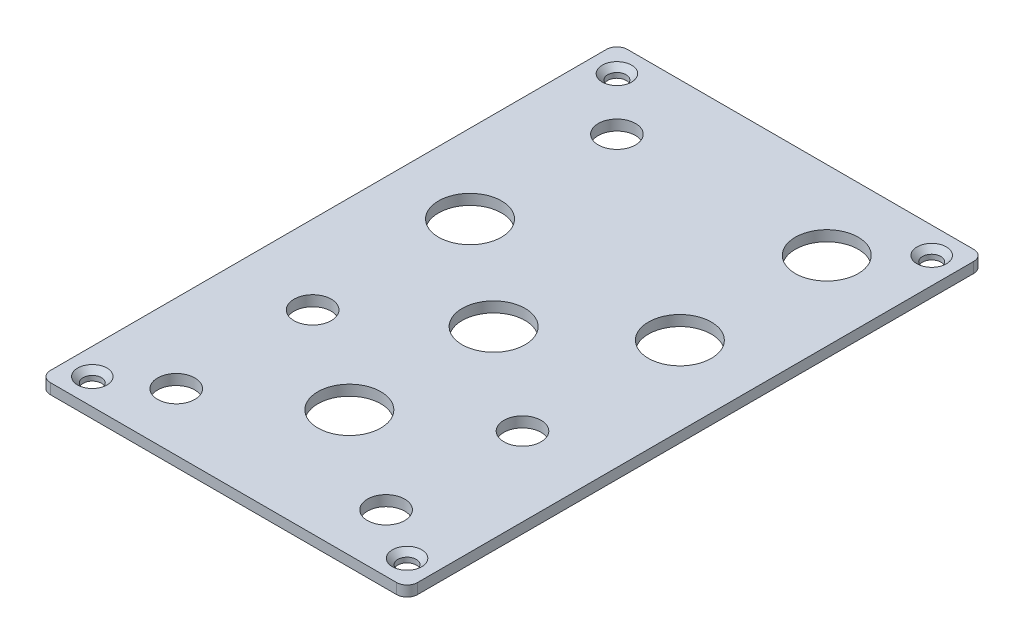
SolidWorks part; units mm, degrees
ref_plane "Front Plane" through (0, 0, 0) normal (0, 0, 1) x (1, 0, 0)
ref_plane "Top Plane" through (0, 0, 0) normal (0, 1, 0) x (1, 0, 0)
ref_plane "Right Plane" through (0, 0, 0) normal (1, 0, 0) x (0, 0, -1)
sketch "Face Plate" plane through (0, 0, 0) normal (0, 1, 0) x (1, 0, 0)
  line L1 (35, -55) -> (-35, -55)
  line L2 (35, -55) -> (35, 55)
  line L3 (35, 55) -> (-35, 55)
  line L4 (-35, -55) -> (-35, 55)
  line L5 (35, -55) -> (-35, 55) construction
  line L6 (35, 55) -> (-35, -55) construction
  point P0 (0, 0)
  dimension "D1" = 70
  dimension "D2" = 110
extrude "Face Plate Ext" add sketch "Face Plate" along normal blind 2
sketch "Buttons" plane through (0, 2, 0) normal (0, 1, 0) x (1, 0, 0)
  line L0 (-20, -18) -> (-20, -44) construction
  line L1 (-35, 55) -> (-35, -55) construction
  line L2 (-20, -31) -> (0, -31) construction
  line L3 (35, 55) -> (-35, 55) construction
  line L4 (35, -55) -> (35, 55) construction
  line L5 (-20, -18) -> (20, -18) construction
  line L6 (0, -18) -> (0, -31) construction
  circle A0 centre (-20, 12) radius 6
  circle A1 centre (20, 12) radius 6
  circle A2 centre (-20, -18) radius 3.55
  circle A3 centre (-20, -44) radius 3.55
  circle A4 centre (-20, 40) radius 3.55
  circle A5 centre (20, -18) radius 3.55
  circle A6 centre (20, -44) radius 3.55
  circle A7 centre (20, 40) radius 6
  circle A8 centre (0, -31) radius 6
  circle A9 centre (0, -3.5) radius 6
  dimension "D6" = 12
  dimension "D7" = 7.1
  dimension "D5" = 7.1
  dimension "D9" = 14.5
  dimension "D2" = 15
  dimension "D3" = 15
  dimension "D4" = 15
  dimension "D8" = 28
  dimension "D10" = 15
  dimension "D11" = 15
  dimension "D12" = 15
  dimension "D13" = 26
  dimension "D14" = 30
extrude "Buttons CUT" cut sketch "Buttons" against normal blind 10
sketch "M3 Top Screw" plane through (0, 2, 0) normal (0, 1, 0) x (1, 0, 0)
  line L0 (-35, 55) -> (-35, -55) construction
  line L1 (35, 55) -> (-35, 55) construction
  line L2 (35, -55) -> (35, 55) construction
  line L3 (-35, -55) -> (35, -55) construction
  circle A0 centre (-30, 50) radius 1.75
  circle A1 centre (30, 50) radius 1.75
  circle A2 centre (-30, -50) radius 1.75
  circle A3 centre (30, -50) radius 1.75
  dimension "D1" = 3.5
  dimension "D2" = 5
  dimension "D3" = 5
  dimension "D4" = 5
  dimension "D5" = 5
extrude "M3 Top Screw CUT" cut sketch "M3 Top Screw" against normal blind 10
sketch "M3 Head Top" plane through (0, 2, 0) normal (0, 1, 0) x (1, 0, 0)
  circle A0 centre (-30, 50) radius 2.8
  circle A1 centre (30, 50) radius 2.8
  circle A2 centre (30, -50) radius 2.8
  circle A3 centre (-30, -50) radius 2.8
  dimension "D1" = 5.6
extrude "M3 Head Top CUT" cut sketch "M3 Head Top" against normal blind 10 draft 45
fillet "Fillet1" radius 2 1 edges at (-35, 1, -55)
fillet "Fillet2" radius 2 1 edges at (35, 1, -55)
fillet "Fillet3" radius 2 1 edges at (35, 1, 55)
fillet "Fillet4" radius 2 1 edges at (-35, 1, 55)
equation "\"SPACER_SIDE\"=15"
equation "\"D10@Buttons\"=\"SPACER_SIDE\""
equation "\"D2@Buttons\"=\"SPACER_SIDE\""
equation "\"D3@Buttons\"=\"SPACER_SIDE\""
equation "\"ENCODER\"=7.1"
equation "\"D7@Buttons\"=\"ENCODER\""
equation "\"D5@Buttons\"=\"ENCODER\""
equation "\"D11@Buttons\"=\"SPACER_SIDE\""
equation "\"D12@Buttons\"=\"SPACER_SIDE\""
equation "\"SCREW_M3\"=3.5"
equation "\"D1@M3 Top Screw\"=\"SCREW_M3\""
equation "\"SPACER_COVER_SCREW\"=5"
equation "\"D2@M3 Top Screw\"=\"SPACER_COVER_SCREW\""
equation "\"D3@M3 Top Screw\"=\"SPACER_COVER_SCREW\""
equation "\"D4@M3 Top Screw\"=\"SPACER_COVER_SCREW\""
equation "\"D5@M3 Top Screw\"=\"SPACER_COVER_SCREW\""
equation "\"SCREW_M3_HEAD\"=5.6"
equation "\"D1@M3 Head Top\"=\"SCREW_M3_HEAD\""
